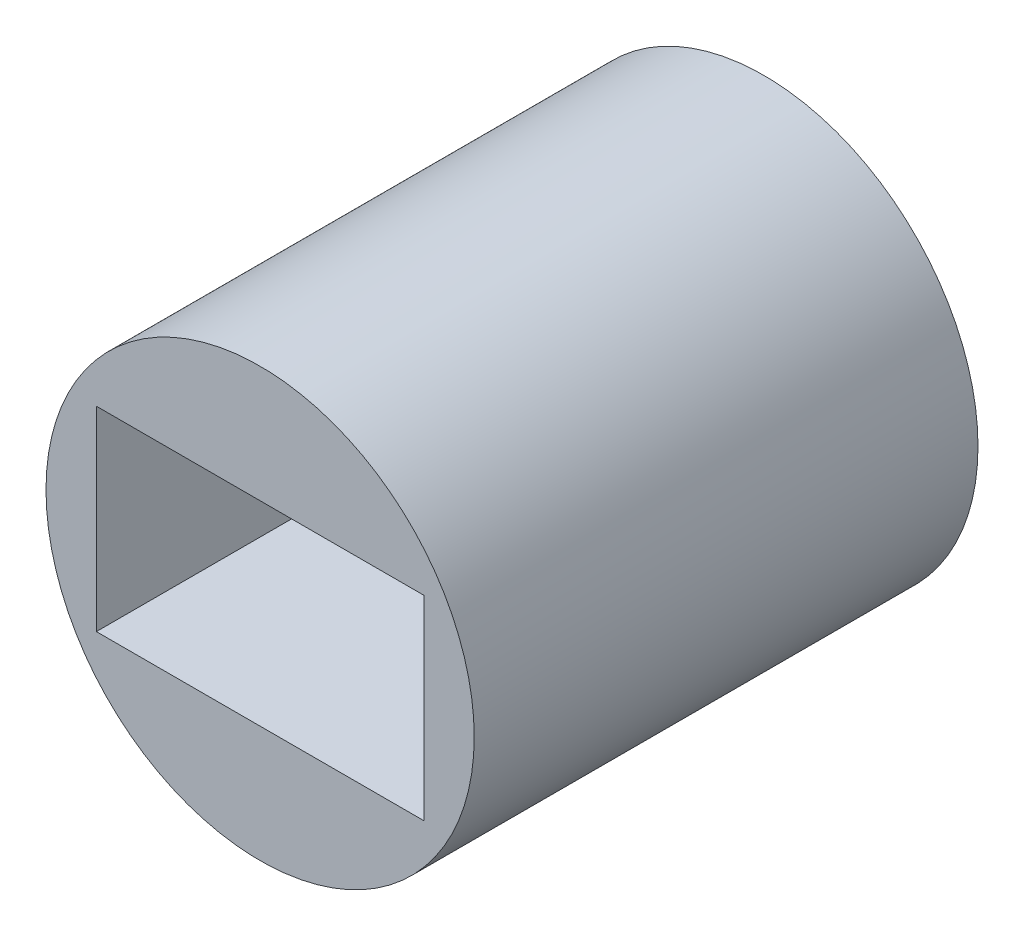
SolidWorks part; units mm, degrees
ref_plane "Alzado" through (0, 0, 0) normal (0, 0, 1) x (1, 0, 0)
ref_plane "Planta" through (0, 0, 0) normal (0, 1, 0) x (1, 0, 0)
ref_plane "Vista lateral" through (0, 0, 0) normal (1, 0, 0) x (0, 0, -1)
sketch "Croquis1" plane through (0, 0, 0) normal (0, 0, 1) x (1, 0, 0)
  line L1 (-2.6, 1.55) -> (2.6, 1.55)
  line L2 (-2.6, 1.55) -> (-2.6, -1.55)
  line L3 (-2.6, -1.55) -> (2.6, -1.55)
  line L4 (2.6, 1.55) -> (2.6, -1.55)
  line L5 (-2.6, 1.55) -> (2.6, -1.55) construction
  line L6 (-2.6, -1.55) -> (2.6, 1.55) construction
  circle A0 centre (0, 0) radius 3.4
  dimension "D1" = 6.8
  dimension "D2" = 3.1
  dimension "D3" = 5.2
extrude "Saliente-Extruir1" add sketch "Croquis1" along normal blind 8
